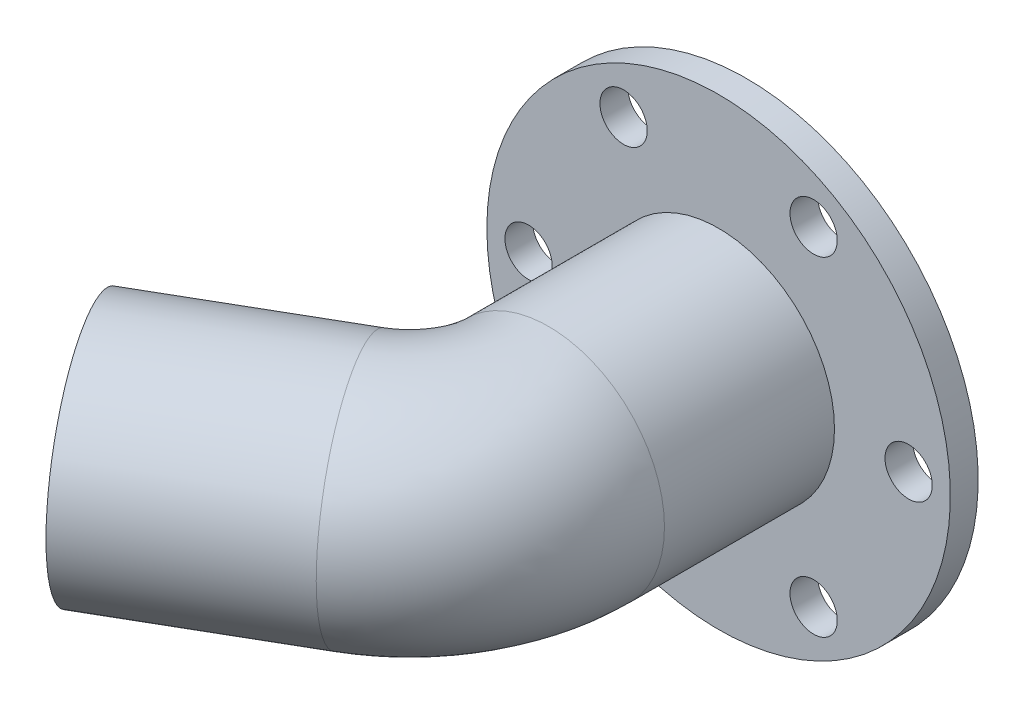
SolidWorks part; units mm, degrees
material "БрАЖ9-4 ГОСТ 18175-78"
ref_plane "Спереди" through (0, 0, 0) normal (0, 0, 1) x (1, 0, 0)
ref_plane "Сверху" through (0, 0, 0) normal (0, 1, 0) x (1, 0, 0)
ref_plane "Справа" through (0, 0, 0) normal (1, 0, 0) x (0, 0, -1)
sketch "Эскиз1" plane through (0, 0, 0) normal (0, 0, 1) x (1, 0, 0)
  circle A0 centre (0, 0) radius 25
  circle A1 centre (0, 0) radius 15
  dimension "D1" = 50
  dimension "D2" = 30
sketch "Эскиз2" plane through (0, 0, 0) normal (0, 1, 0) x (1, 0, 0)
  line L0 (0, 0) -> (0, -62.6795)
  line L1 (-25, 0) -> (25, 0) construction
  line L2 (-15, -88.6603) -> (-51.9615, -110)
  line L3 (0, -80) -> (-40.494, -80) construction
  arc A0 (0, -62.6795) -> (-15, -88.6603) centre (-30, -62.6795) cw
  dimension "D4" = 30
  dimension "D1" = 80
  dimension "D2" = 30
  dimension "D3" = 60
sweep "По траектории1" add profiles "Эскиз1" path "Эскиз2"
sketch "Эскиз3" plane through (0, 0, 0) normal (0, 0, -1) x (-1, 0, 0)
  circle A0 centre (0, 0) radius 36
  circle A1 centre (0, 0) radius 25
  circle A2 centre (0, 0) radius 25 construction
  dimension "D1" = 72
extrude "Бобышка-Вытянуть2" add sketch "Эскиз3" against normal blind 5 from offset 20 offset against normal yes
sketch "Эскиз4" plane through (0, 0, 0) normal (0, 1, 0) x (1, 0, 0)
  line L0 (36, -20) -> (-36, -20) construction
  line L1 (22, -16) -> (32, -16)
  line L2 (22, -16) -> (22, -20)
  line L3 (22, -20) -> (32, -20)
  line L4 (32, -16) -> (32, -20)
  line L5 (0, 0) -> (0, -25) construction
  line L6 (25, 0) -> (-25, 0) construction
  line L7 (-25, -25) -> (25, -25) construction
  dimension "D1" = 44
  dimension "D2" = 10
  dimension "D3" = 4
revolve "Вырез-Повернуть1" cut sketch "Эскиз4" angle 360 about L5
sketch "Эскиз5" plane through (0, 0, 0) normal (0, 0, -1) x (-1, 0, 0)
  circle A0 centre (0, 0) radius 25 construction
  circle A1 centre (0, 0) radius 25
extrude "Вырез-Вытянуть1" cut sketch "Эскиз5" against normal up to surface (20 mm away) up to face at (-36, 0, 20)
sketch "Эскиз6" plane through (0, 0, 20) normal (0, 0, -1) x (-1, 0, 0)
  circle A0 centre (0, 0) radius 50
  circle A1 centre (0, 0) radius 15 construction
  circle A2 centre (0, 0) radius 15
  dimension "D1" = 100
extrude "Бобышка-Вытянуть3" add sketch "Эскиз6" against normal blind 6
sketch "Эскиз7" plane through (0, 0, 20) normal (0, 0, -1) x (-1, 0, 0)
  line L0 (0, 0) -> (-50, 0) construction
  circle A0 centre (0, 0) radius 50 construction
  circle A1 centre (-41, 0) radius 5.1
  dimension "D1" = 10.2
  dimension "D2" = 41
extrude "Вырез-Вытянуть2" cut sketch "Эскиз7" against normal up to next
pattern_circular "Круговой массив1" count 6 over 360 about axis through (0, 0, 0) along (0, 0, 1) of "Вырез-Вытянуть2"
